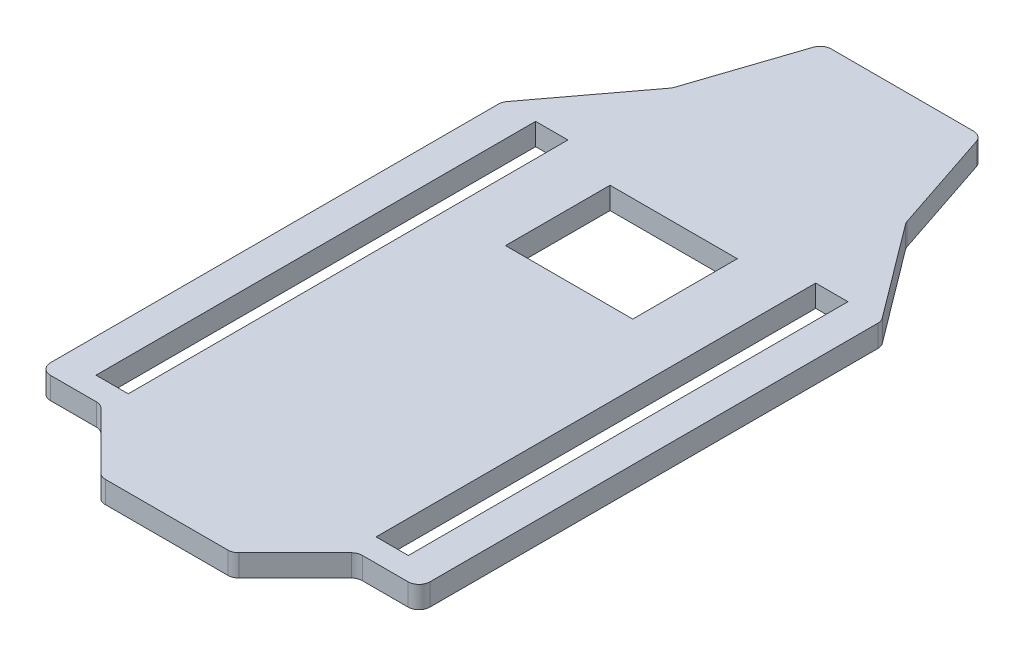
SolidWorks part; units mm, degrees
ref_plane "Front Plane" through (0, 0, 0) normal (0, 0, 1) x (1, 0, 0)
ref_plane "Top Plane" through (0, 0, 0) normal (0, 1, 0) x (1, 0, 0)
ref_plane "Right Plane" through (0, 0, 0) normal (1, 0, 0) x (0, 0, -1)
sketch "Sketch1" plane through (0, 0, 0) normal (0, 1, 0) x (1, 0, 0)
  line L0 (0, 5) -> (0, 209.0943)
  line L1 (0, 210.761) -> (-33.2302, 210.761) construction
  line L2 (-33.2302, 210.761) -> (-33.2302, 255.068) construction
  line L3 (-33.2302, 255.068) -> (-50.4378, 255.068) construction
  line L4 (-50.4378, 255.068) -> (-50.4378, 306.6907) construction
  line L5 (-54.0416, 306.6907) -> (-118.8873, 306.6907)
  line L6 (-86.4645, 306.6907) -> (-86.4645, -147.8249) construction
  line L7 (-1, 212.0943) -> (-32.7434, 254.4189)
  line L8 (-33.4868, 255.8377) -> (-49.2982, 303.2719)
  line L9 (-5, 0) -> (-25.8579, 0)
  line L10 (-116.4645, 0) -> (-116.4645, -28.5355) construction
  line L11 (-15.2965, 210.761) -> (-30, 210.761)
  line L12 (-15.2965, 210.761) -> (-15.2965, 10.4276)
  line L13 (-15.2965, 10.4276) -> (-30, 10.4276)
  line L14 (-30, 210.761) -> (-30, 10.4276)
  line L15 (-27.9289, 0) -> (-56.4645, 0) construction
  line L16 (-56.4645, 0) -> (-56.4645, -28.5355) construction
  line L17 (-55, -27.0711) -> (-29.3934, -1.4645)
  line L18 (-58.5355, -28.5355) -> (-114.3934, -28.5355)
  line L19 (-145, 0) -> (-116.4645, 0) construction
  line L20 (-122.4911, 255.068) -> (-122.4911, 306.6907) construction
  line L21 (-139.6987, 255.068) -> (-122.4911, 255.068) construction
  line L22 (-139.6987, 210.761) -> (-139.6987, 255.068) construction
  line L23 (-172.9289, 210.761) -> (-139.6987, 210.761) construction
  line L24 (-117.9289, -27.0711) -> (-143.5355, -1.4645)
  line L25 (-142.9289, 210.761) -> (-142.9289, 10.4276)
  line L26 (-157.6324, 10.4276) -> (-142.9289, 10.4276)
  line L27 (-157.6324, 210.761) -> (-157.6324, 10.4276)
  line L28 (-157.6324, 210.761) -> (-142.9289, 210.761)
  line L29 (-167.9289, 0) -> (-147.0711, 0)
  line L30 (-139.4421, 255.8377) -> (-123.6307, 303.2719)
  line L31 (-171.9289, 212.0943) -> (-140.1855, 254.4189)
  line L32 (-172.9289, 5) -> (-172.9289, 209.0943)
  line L33 (-30, 210.761) -> (-57.4669, 210.761) construction
  line L34 (-57.4669, 210.761) -> (-57.4669, 202.5) construction
  line L35 (-142.9289, 210.761) -> (-115.462, 210.761) construction
  line L36 (-115.462, 210.761) -> (-115.462, 202.5) construction
  line L37 (-115.462, 202.5) -> (-115.462, 154.8653) construction
  line L39 (-57.4669, 202.5) -> (-115.462, 202.5)
  line L40 (-57.4669, 202.5) -> (-57.4669, 154.8653)
  line L41 (-57.4669, 154.8653) -> (-115.462, 154.8653)
  line L42 (-115.462, 202.5) -> (-115.462, 154.8653)
  arc A0 (-29.3934, -1.4645) -> (-25.8579, 0) centre (-25.8579, -5) cw
  arc A1 (-33.4868, 255.8377) -> (-32.7434, 254.4189) centre (-28.7434, 257.4189) ccw
  arc A2 (-1, 212.0943) -> (0, 209.0943) centre (-5, 209.0943) cw
  arc A3 (0, 5) -> (-5, 0) centre (-5, 5) cw
  arc A4 (-58.5355, -28.5355) -> (-55, -27.0711) centre (-58.5355, -23.5355) ccw
  arc A5 (-54.0416, 306.6907) -> (-49.2982, 303.2719) centre (-54.0416, 301.6907) cw
  arc A6 (-118.8873, 306.6907) -> (-123.6307, 303.2719) centre (-118.8873, 301.6907) ccw
  arc A7 (-114.3934, -28.5355) -> (-117.9289, -27.0711) centre (-114.3934, -23.5355) cw
  arc A8 (-172.9289, 5) -> (-167.9289, 0) centre (-167.9289, 5) ccw
  arc A9 (-171.9289, 212.0943) -> (-172.9289, 209.0943) centre (-167.9289, 209.0943) ccw
  arc A10 (-139.4421, 255.8377) -> (-140.1855, 254.4189) centre (-144.1855, 257.4189) cw
  arc A11 (-143.5355, -1.4645) -> (-147.0711, 0) centre (-147.0711, -5) ccw
  point P28 (0, 0)
  point P37 (-86.4645, -28.5355)
  point P65 (-172.9289, 0)
  dimension "D1" = 5
  dimension "D2" = 5
extrude "Boss-Extrude1" add sketch "Sketch1" along normal blind 10
